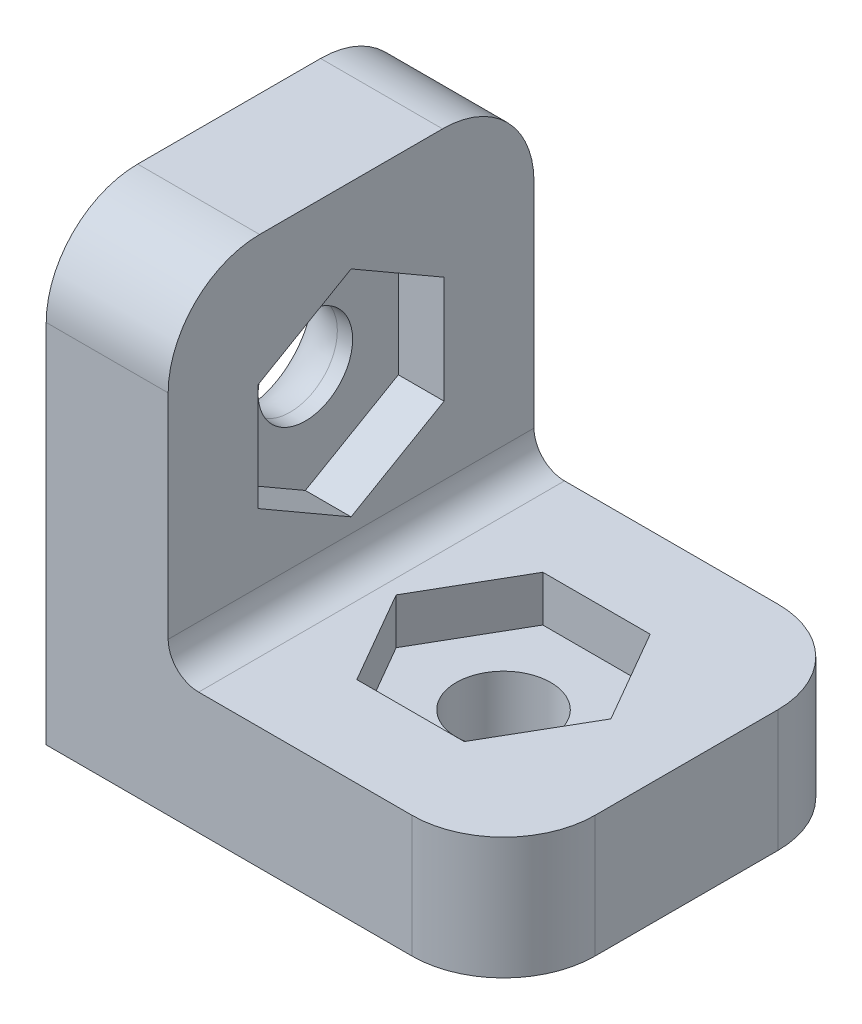
SolidWorks part; units mm, degrees
ref_plane "Front Plane" through (0, 0, 0) normal (0, 0, 1) x (1, 0, 0)
ref_plane "Top Plane" through (0, 0, 0) normal (0, 1, 0) x (1, 0, 0)
ref_plane "Right Plane" through (0, 0, 0) normal (1, 0, 0) x (0, 0, -1)
sketch "Sketch1" plane through (0, 0, 0) normal (0, 0, 1) x (1, 0, 0)
  line L0 (0, 0) -> (0, 15)
  line L1 (0, 15) -> (4, 15)
  line L2 (4, 15) -> (4, 4)
  line L3 (4, 4) -> (15, 4)
  line L4 (15, 4) -> (15, 0)
  line L5 (15, 0) -> (0, 0)
  dimension "D1" = 15
  dimension "D2" = 15
  dimension "D3" = 4
  dimension "D4" = 4
extrude "Boss-Extrude1" add sketch "Sketch1" along normal blind 12
sketch "Sketch2" plane through (0, 4, 0) normal (0, 1, 0) x (1, 0, 0)
  circle A0 centre (9, -6) radius 1.55
  dimension "D1" = 3.1
extrude "Cut-Extrude1" cut sketch "Sketch2" against normal through all
sketch "Sketch3" plane through (0, 4, 0) normal (0, 1, 0) x (1, 0, 0)
  line L1 (5.4782, -6) -> (7.2391, -9.05)
  line L2 (7.2391, -9.05) -> (10.7609, -9.05)
  line L3 (10.7609, -9.05) -> (12.5218, -6)
  line L4 (12.5218, -6) -> (10.7609, -2.95)
  line L5 (10.7609, -2.95) -> (7.2391, -2.95)
  line L6 (7.2391, -2.95) -> (5.4782, -6)
  circle A0 centre (9, -6) radius 3.05 construction
extrude "Cut-Extrude2" cut sketch "Sketch3" against normal blind 1.5
sketch "Sketch4" plane through (4, 0, 0) normal (1, 0, 0) x (0, 0, -1)
  circle A0 centre (-6, 9) radius 1.55
  dimension "D1" = 3.1
extrude "Cut-Extrude3" cut sketch "Sketch4" against normal through all
sketch "Sketch5" plane through (4, 0, 0) normal (1, 0, 0) x (0, 0, -1)
  line L1 (-6, 5.4782) -> (-2.95, 7.2391)
  line L2 (-2.95, 7.2391) -> (-2.95, 10.7609)
  line L3 (-2.95, 10.7609) -> (-6, 12.5218)
  line L4 (-6, 12.5218) -> (-9.05, 10.7609)
  line L5 (-9.05, 10.7609) -> (-9.05, 7.2391)
  line L6 (-9.05, 7.2391) -> (-6, 5.4782)
  circle A0 centre (-6, 9) radius 3.05 construction
extrude "Cut-Extrude4" cut sketch "Sketch5" against normal blind 1.5
fillet "Fillet1" radius 2 1 edges at (0, 10.55, 6)
fillet "Fillet2" radius 1 1 edges at (4, 4, 6)
fillet "Fillet3" radius 3 4 edges at (15, 2, 0) (15, 2, 12) (2, 15, 12) (2, 15, 0)
